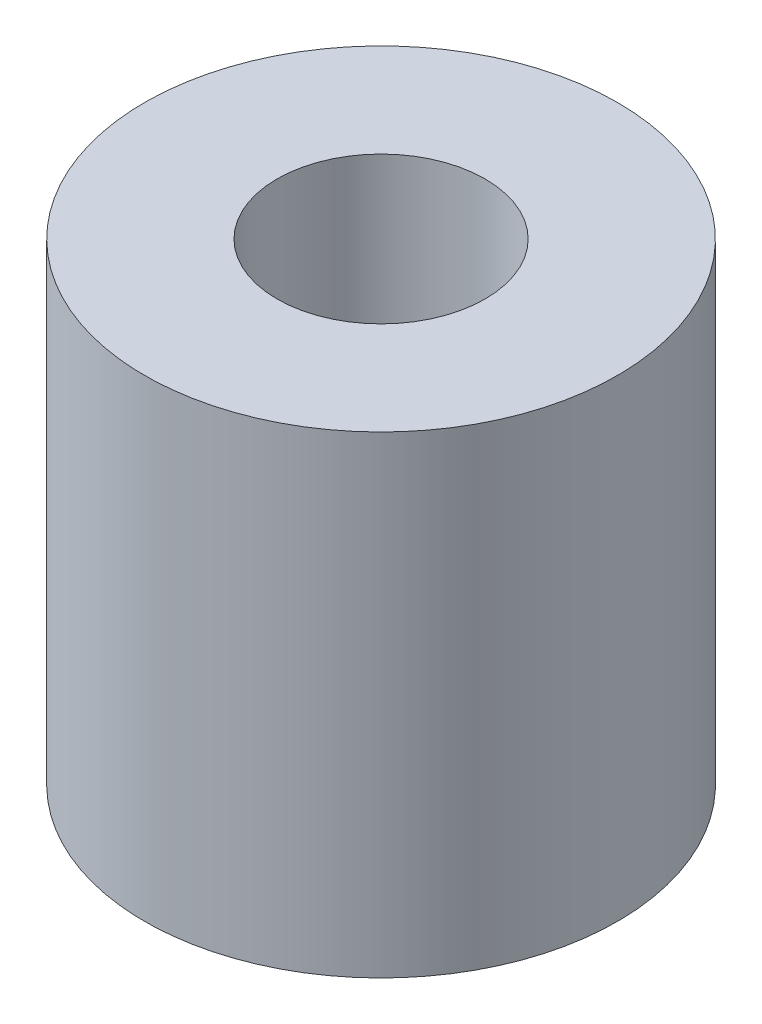
SolidWorks part; units mm, degrees
material "Nylon 101"
ref_plane "Front Plane" through (0, 0, 0) normal (0, 0, 1) x (1, 0, 0)
ref_plane "Top Plane" through (0, 0, 0) normal (0, 1, 0) x (1, 0, 0)
ref_plane "Right Plane" through (0, 0, 0) normal (1, 0, 0) x (0, 0, -1)
other "1/32"
sketch "Sketch1" plane through (0, 0, 0) normal (0, 1, 0) x (1, 0, 0)
  circle A0 centre (0, 0) radius 2.0955
  circle A1 centre (0, 0) radius 4.7625
  dimension "D1" = 4.191
  dimension "D2" = 9.525
extrude "Boss-Extrude1" add sketch "Sketch1" along normal blind 9.525
